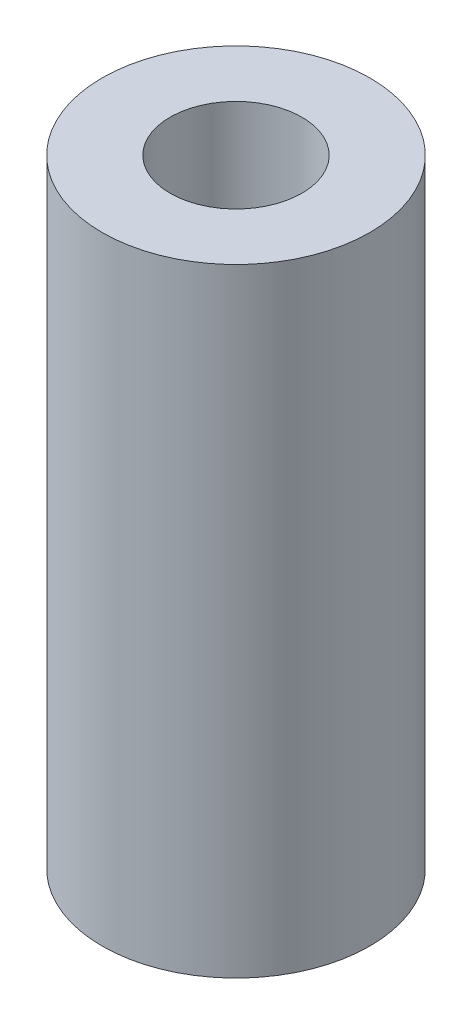
SolidWorks part; units mm, degrees
ref_plane "Front Plane" through (0, 0, 0) normal (0, 0, 1) x (1, 0, 0)
ref_plane "Top Plane" through (0, 0, 0) normal (0, 1, 0) x (1, 0, 0)
ref_plane "Right Plane" through (0, 0, 0) normal (1, 0, 0) x (0, 0, -1)
sketch "Sketch1" plane through (0, 0, 0) normal (0, 1, 0) x (1, 0, 0)
  circle A0 centre (0, 0) radius 1.6
  circle A1 centre (0, 0) radius 3.25
  dimension "D1" = 3.2
  dimension "D2" = 6.5
extrude "Boss-Extrude1" add sketch "Sketch1" along normal blind 15
